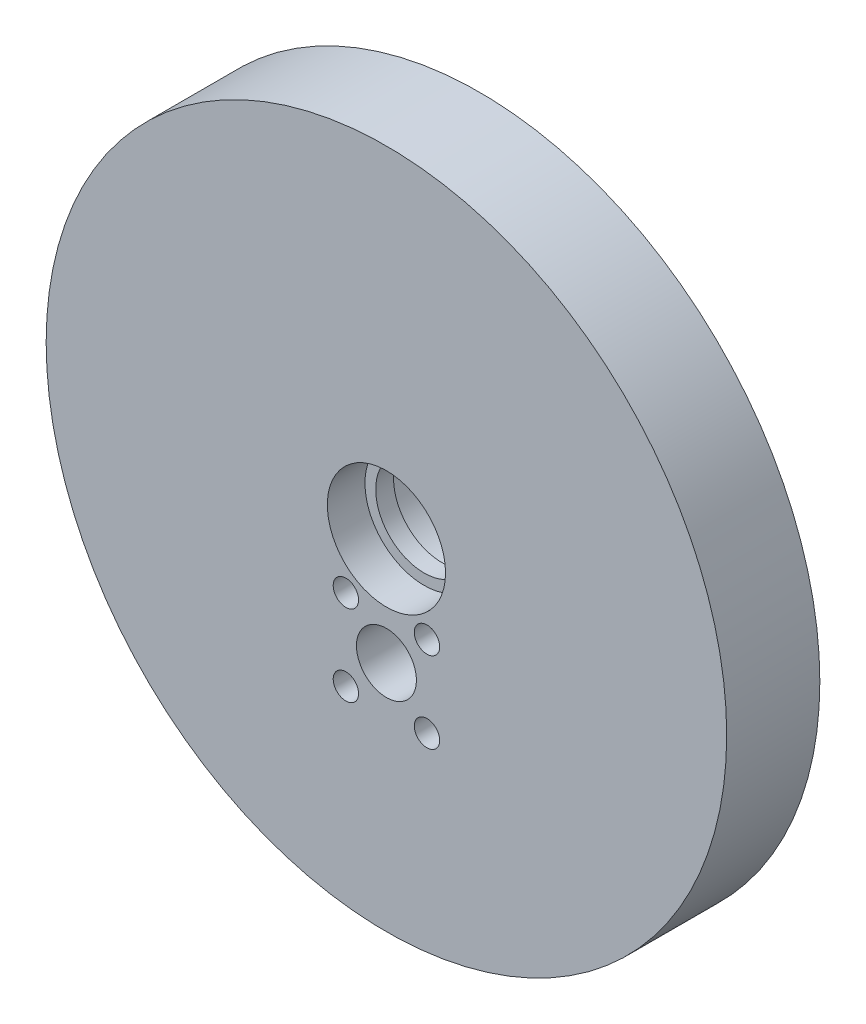
SolidWorks part; units mm, degrees
ref_plane "Front Plane" through (0, 0, 0) normal (0, 0, 1) x (1, 0, 0)
ref_plane "Top Plane" through (0, 0, 0) normal (0, 1, 0) x (1, 0, 0)
ref_plane "Right Plane" through (0, 0, 0) normal (1, 0, 0) x (0, 0, -1)
sketch "Sketch1" plane through (0, 0, 0) normal (0, 0, 1) x (1, 0, 0)
  circle A0 centre (0, 0) radius 48.26
  dimension "D1" = 96.52
extrude "Boss-Extrude1" add sketch "Sketch1" along normal blind 13.208
sketch "Sketch2" plane through (0, 0, 13.208) normal (0, 0, 1) x (1, 0, 0)
  circle A0 centre (0, 0) radius 8.382
  dimension "D1" = 16.764
extrude "Cut-Extrude1" cut sketch "Sketch2" against normal blind 5.334
sketch "Sketch3" plane through (0, 0, 13.208) normal (0, 0, 1) x (1, 0, 0)
  line L0 (0, -41.275) -> (0, 41.275) construction
  circle A1 centre (0, 41.275) radius 3.429
  circle A2 centre (0, -41.275) radius 3.429
  point P5 (0, 0)
  dimension "D2" = 6.858
  dimension "D1" = 82.55
sketch "Sketch12" plane through (0, 0, 0) normal (0, 0, -1) x (-1, 0, 0)
  circle A0 centre (0, -15.24) radius 4.25
  dimension "D2" = 8.5
  dimension "D1" = 15.24
extrude "Cut-Extrude5" cut sketch "Sketch12" against normal through all
extrude "Cut-Extrude6" [suppressed] cut sketch "Sketch3" against normal blind 6.35
sketch "Sketch13" plane through (0, 0, 0) normal (0, 0, -1) x (-1, 0, 0)
  line L0 (-5.75, -9.49) -> (5.75, -20.99) construction
  line L1 (-5.75, -9.49) -> (5.75, -9.49)
  line L2 (-5.75, -9.49) -> (-5.75, -20.99)
  line L3 (-5.75, -20.99) -> (5.75, -20.99)
  line L4 (5.75, -9.49) -> (5.75, -20.99)
  line L5 (-5.75, -20.99) -> (5.75, -9.49) construction
  circle A0 centre (5.75, -9.49) radius 1.8
  circle A1 centre (5.75, -20.99) radius 1.8
  circle A2 centre (-5.75, -20.99) radius 1.8
  circle A3 centre (-5.75, -9.49) radius 1.8
  point P4 (0, -15.24)
  dimension "D4" = 3.6
  dimension "D1" = 11.5
  dimension "D2" = 15.24
  dimension "D3" = 11.5
extrude "Cut-Extrude7" cut sketch "Sketch13" against normal through all contours A0 | A1 | A2 | A3
ref_plane "Mid Plane" through (0, 0, 6.604) normal (0, 0, 1) x (1, 0, 0)
mirror "Mirror1" about plane through (0, 0, 6.604) normal (0, 0, 1) of "Cut-Extrude1"
sketch "Sketch14" plane through (0, 0, 13.208) normal (0, 0, 1) x (1, 0, 0)
  circle A0 centre (0, 0) radius 6.858
  circle A1 centre (0, 0) radius 48.26 construction
  circle A2 centre (0, 0) radius 8.382 construction
  dimension "D1" = 1.524
extrude "Cut-Extrude8" cut sketch "Sketch14" against normal through all
